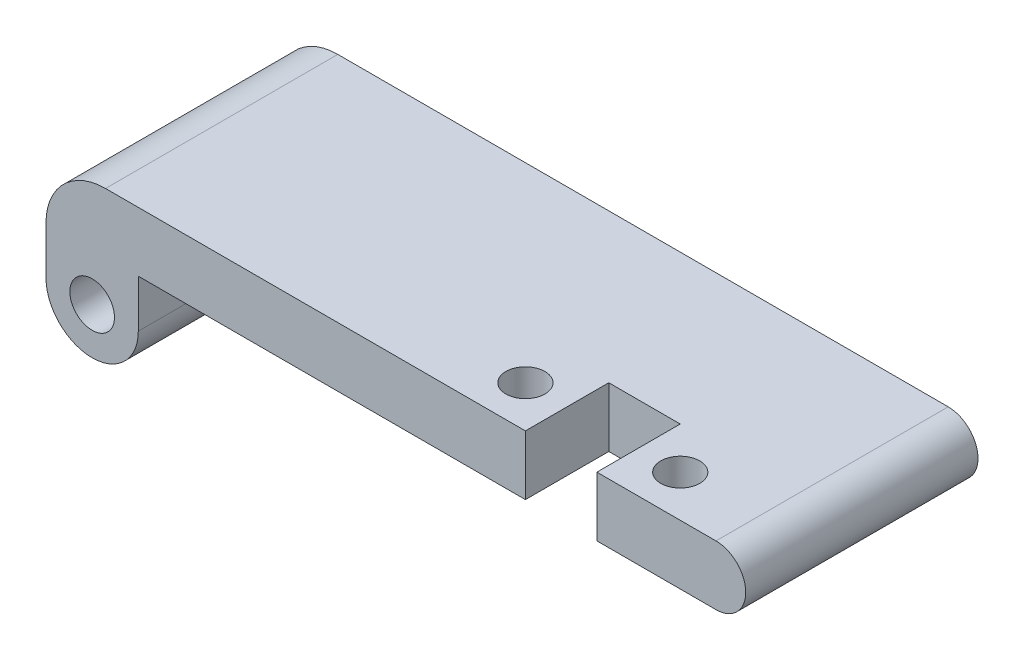
SolidWorks part; units mm, degrees
ref_plane "Front Plane" through (0, 0, 0) normal (0, 0, 1) x (1, 0, 0)
ref_plane "Top Plane" through (0, 0, 0) normal (0, 1, 0) x (1, 0, 0)
ref_plane "Right Plane" through (0, 0, 0) normal (1, 0, 0) x (0, 0, -1)
sketch "Sketch1" plane through (0, 0, 0) normal (0, 0, 1) x (1, 0, 0)
  line L0 (-37.3856, -8.255) -> (-37.3856, -3.175)
  line L1 (-37.3856, 3.175) -> (37.3856, 3.175)
  line L2 (-37.3856, 3.175) -> (-37.3856, -3.175)
  line L3 (-27.5431, -3.175) -> (37.3856, -3.175)
  line L4 (37.3856, 3.175) -> (37.3856, -3.175)
  line L5 (-37.3856, 3.175) -> (37.3856, -3.175) construction
  line L6 (-37.3856, -3.175) -> (37.3856, 3.175) construction
  line L7 (-27.5431, -8.255) -> (-27.5431, -3.175)
  circle A0 centre (-32.4644, -8.255) radius 2.3812
  arc A1 (-37.3856, -8.255) -> (-27.5431, -8.255) centre (-32.4644, -8.255) ccw
  point P0 (0, 0)
  dimension "D1" = 4.7625
  dimension "D3" = 2.54
  dimension "D2" = 6.35
  dimension "D4" = 69.85
  dimension "D5" = 5.08
extrude "Boss-Extrude1" add sketch "Sketch1" along normal blind 38.1
fillet "Fillet1" radius 6.35 1 edges at (-37.3856, 3.175, 19.05)
sketch "Sketch3" plane through (37.3856, 0, 0) normal (1, 0, 0) x (0, 0, -1)
  line L4 (0, -3.175) -> (0, 3.175)
  line L5 (0, 3.175) -> (-38.1, 3.175)
  line L6 (-38.1, 3.175) -> (-38.1, -3.175)
  line L7 (-38.1, -3.175) -> (0, -3.175)
  line L8 (0, -3.175) -> (0, 3.175)
  line L9 (0, 3.175) -> (-38.1, 3.175)
  line L10 (-38.1, 3.175) -> (-38.1, -3.175)
  line L11 (-38.1, -3.175) -> (0, -3.175)
  dimension "D1" = 0
extrude "Boss-Extrude2" add sketch "Sketch3" along normal blind 12.7
sketch "Sketch2" plane through (0, 3.175, 0) normal (0, 1, 0) x (1, 0, 0)
  line L1 (48.4981, -15.875) -> (11.9856, -15.875) construction
  line L2 (48.4981, -15.875) -> (48.4981, 0) construction
  line L3 (48.4981, 0) -> (11.9856, 0) construction
  line L4 (11.9856, -15.875) -> (11.9856, 0) construction
  line L5 (48.4981, -15.875) -> (11.9856, 0) construction
  line L6 (48.4981, 0) -> (11.9856, -15.875) construction
  line L7 (11.9856, -17.4625) -> (-16.5894, -17.4625) construction
  line L8 (11.9856, -17.4625) -> (11.9856, 1.5875) construction
  line L9 (11.9856, 1.5875) -> (-16.5894, 1.5875) construction
  line L10 (-16.5894, -17.4625) -> (-16.5894, 1.5875) construction
  line L11 (11.9856, -17.4625) -> (-16.5894, 1.5875) construction
  line L12 (11.9856, 1.5875) -> (-16.5894, -17.4625) construction
  line L13 (37.3856, -25.4) -> (37.3856, 9.525) construction
  line L14 (50.0856, 0) -> (-31.0356, 0) construction
  line L15 (-34.8456, -38.1) -> (-30.0831, -38.1) construction
  line L16 (-34.8456, -38.1) -> (-30.0831, -38.1) construction
  line L18 (21.3519, -24.765) -> (13.7319, -24.765)
  line L19 (21.3519, -24.765) -> (21.3519, -15.875)
  line L20 (21.3519, -15.875) -> (13.7319, -15.875)
  line L21 (13.7319, -24.765) -> (13.7319, -15.875)
  line L22 (21.3519, -24.765) -> (13.7319, -15.875) construction
  line L23 (21.3519, -15.875) -> (13.7319, -24.765) construction
  point P0 (30.2419, -7.9375)
  point P5 (17.5419, -20.32)
  point P6 (-2.3019, -7.9375)
  point P15 (17.5419, -20.32)
  point P21 (-32.4644, -38.1)
  point P26 (37.3856, -7.9375)
  dimension "Motor_Pos" = 15.875
  dimension "D2" = 36.5125
  dimension "D3" = 28.575
  dimension "D4" = 19.05
  dimension "D5" = 5.5562
  dimension "D6" = 11.1125
  dimension "D7" = 34.925
  dimension "D8" = 69.85
  dimension "D9" = 8.89
  dimension "D10" = 7.62
extrude "Cut-Extrude7" cut sketch "Sketch2" against normal through all
sketch "Sketch10" plane through (0, 3.175, 0) normal (0, 1, 0) x (1, 0, 0)
  line L0 (13.7319, -24.765) -> (13.7319, -15.875) construction
  line L1 (21.3519, -24.765) -> (13.7319, -24.765) construction
  line L2 (21.3519, -24.765) -> (21.3519, -15.875) construction
  line L3 (21.3519, -15.875) -> (13.7319, -15.875) construction
  line L12 (13.7319, -24.765) -> (13.7319, -15.875)
  line L13 (21.3519, -24.765) -> (13.7319, -24.765)
  line L14 (21.3519, -24.765) -> (21.3519, -15.875)
  line L15 (21.3519, -15.875) -> (13.7319, -15.875)
extrude "Boss-Extrude5" add sketch "Sketch10" along normal blind 22.225 and the other way blind 9.525
sketch "Sketch5" plane through (0, 0, 24.765) normal (0, 0, 1) x (1, 0, 0)
  line L0 (17.5419, 25.4) -> (17.5419, -6.35) construction
  line L3 (13.7319, -6.35) -> (21.3519, -6.35) construction
  line L4 (13.7319, 25.4) -> (21.3519, 25.4) construction
  circle A0 centre (17.5419, 5.715) radius 1.905
  circle A1 centre (17.5419, 23.1775) radius 1.905
  dimension "D1" = 3.81
  dimension "D2" = 17.4625
  dimension "D3" = 12.065
extrude "Cut-Extrude1" cut sketch "Sketch5" against normal through all both and the other way through all
sketch "Sketch6" plane through (0, -3.175, 0) normal (0, 1, 0) x (1, 0, 0)
  line L1 (30.2419, -24.765) -> (4.8419, -24.765)
  line L2 (30.2419, -24.765) -> (30.2419, -15.875)
  line L3 (30.2419, -15.875) -> (4.8419, -15.875)
  line L4 (4.8419, -24.765) -> (4.8419, -15.875)
  line L5 (30.2419, -24.765) -> (4.8419, -15.875) construction
  line L6 (30.2419, -15.875) -> (4.8419, -24.765) construction
  line L9 (4.8419, -24.765) -> (30.2419, -24.765) construction
  line L11 (21.3519, -15.875) -> (13.7319, -15.875) construction
  line L12 (21.3519, -24.765) -> (13.7319, -24.765) construction
  line L13 (21.3519, -24.765) -> (13.7319, -24.765)
  line L14 (13.7319, -24.765) -> (13.7319, -15.875) construction
  point P0 (17.5419, -20.32)
  point P14 (17.5419, -24.765)
  point P16 (17.5419, -24.765)
  line M22 (13.7319, -15.875) -> (13.7319, -24.765)
  line M24 (21.3519, -24.765) -> (21.3519, -15.875)
  dimension "D1" = 25.4
  dimension "D2" = 8.89
  dimension "D3" = 8.89
extrude "Boss-Extrude4" add sketch "Sketch6" against normal up to surface (3.175 mm away) contours L1 L4 L3 M22 | L3 L2 L1 M24 up to face at (17.5419, -6.35, 20.32)
sketch "Sketch7" plane through (0, -6.35, 0) normal (0, -1, 0) x (-1, 0, 0)
  line L1 (-4.8419, -24.765) -> (-13.7319, -24.765) construction
  line L2 (-4.8419, -24.765) -> (-4.8419, -15.875) construction
  line L3 (-4.8419, -15.875) -> (-13.7319, -15.875) construction
  line L4 (-13.7319, -24.765) -> (-13.7319, -15.875) construction
  line L5 (-4.8419, -24.765) -> (-13.7319, -15.875) construction
  line L6 (-4.8419, -15.875) -> (-13.7319, -24.765) construction
  line L10 (-17.5419, -24.765) -> (-17.5419, -15.875) construction
  line L12 (-4.8419, -24.765) -> (-30.2419, -24.765) construction
  line L13 (-30.2419, -15.875) -> (-4.8419, -15.875) construction
  line L14 (-4.8419, -24.765) -> (-4.8419, -15.875) construction
  line L15 (-21.3519, -24.765) -> (-21.3519, -15.875) construction
  line L16 (-13.7319, -24.765) -> (-21.3519, -24.765) construction
  line L17 (-13.7319, -15.875) -> (-13.7319, -24.765) construction
  line L18 (-21.3519, -15.875) -> (-13.7319, -15.875) construction
  line L19 (-21.3519, -24.765) -> (-21.3519, -15.875) construction
  line L20 (-13.7319, -24.765) -> (-21.3519, -24.765) construction
  line L21 (-13.7319, -15.875) -> (-13.7319, -24.765) construction
  line L22 (-21.3519, -15.875) -> (-13.7319, -15.875) construction
  circle A0 centre (-9.2869, -20.32) radius 2.0828
  circle A2 centre (-25.7969, -20.32) radius 2.0828
  point P14 (-17.5419, -24.765)
  dimension "D1" = 4.1656
extrude "Cut-Extrude2" cut sketch "Sketch7" against normal through all both and the other way through all
ref_plane "Plane1" through (-27.5431, -3.175, 38.1) normal (1, 0, 0) x (0, 0, -1)
sketch "Sketch9" plane through (0, 0, 38.1) normal (0, 0, 1) x (1, 0, 0)
  line L0 (50.0856, 3.175) -> (50.0856, -3.175) construction
  line L1 (-27.5431, -3.175) -> (50.0856, -3.175) construction
  line L2 (-27.5431, -8.255) -> (-27.5431, -3.175) construction
  line L3 (-37.3856, -3.175) -> (-37.3856, -8.255) construction
  line L4 (50.0856, 3.175) -> (-31.0356, 3.175) construction
  line L5 (50.0856, 3.175) -> (50.0856, -3.175)
  line L6 (-27.5431, -3.175) -> (50.0856, -3.175)
  line L7 (-27.5431, -8.255) -> (-27.5431, -3.175)
  line L8 (-37.3856, -3.175) -> (-37.3856, -8.255)
  line L9 (50.0856, 3.175) -> (-31.0356, 3.175)
  arc A0 (-37.3856, -8.255) -> (-27.5431, -8.255) centre (-32.4644, -8.255) ccw construction
  arc A1 (-31.0356, 3.175) -> (-37.3856, -3.175) centre (-31.0356, -3.175) ccw construction
  arc A2 (-37.3856, -8.255) -> (-27.5431, -8.255) centre (-32.4644, -8.255) ccw
  arc A3 (-31.0356, 3.175) -> (-37.3856, -3.175) centre (-31.0356, -3.175) ccw
extrude "Cut-Extrude8" cut sketch "Sketch9" against normal up to surface (13.335 mm away) up to face at (19.4469, 5.715, 24.765)
sketch "Sketch11" plane through (0, 25.4, 0) normal (0, 1, 0) x (1, 0, 0)
  line L4 (13.7319, -24.765) -> (21.3519, -24.765)
  line L5 (21.3519, -24.765) -> (21.3519, -15.875)
  line L6 (21.3519, -15.875) -> (13.7319, -15.875)
  line L7 (13.7319, -15.875) -> (13.7319, -24.765)
  line L8 (13.7319, -24.765) -> (21.3519, -24.765)
  line L9 (21.3519, -24.765) -> (21.3519, -15.875)
  line L10 (21.3519, -15.875) -> (13.7319, -15.875)
  line L11 (13.7319, -15.875) -> (13.7319, -24.765)
  dimension "D1" = 0
extrude "Cut-Extrude9" cut sketch "Sketch11" against normal through all
sketch "Sketch12" plane through (0, -6.35, 0) normal (0, -1, 0) x (1, 0, 0)
  line L4 (13.7319, 15.875) -> (13.7319, 24.765)
  line L5 (13.7319, 24.765) -> (4.8419, 24.765)
  line L6 (4.8419, 24.765) -> (4.8419, 15.875)
  line L7 (4.8419, 15.875) -> (13.7319, 15.875)
  line L8 (13.7319, 15.875) -> (13.7319, 24.765)
  line L9 (13.7319, 24.765) -> (4.8419, 24.765)
  line L10 (4.8419, 24.765) -> (4.8419, 15.875)
  line L11 (4.8419, 15.875) -> (13.7319, 15.875)
  line L12 (21.3519, 24.765) -> (21.3519, 15.875)
  line L13 (21.3519, 15.875) -> (30.2419, 15.875)
  line L14 (30.2419, 15.875) -> (30.2419, 24.765)
  line L15 (30.2419, 24.765) -> (21.3519, 24.765)
  line L16 (21.3519, 24.765) -> (21.3519, 15.875)
  line L17 (21.3519, 15.875) -> (30.2419, 15.875)
  line L18 (30.2419, 15.875) -> (30.2419, 24.765)
  line L19 (30.2419, 24.765) -> (21.3519, 24.765)
  dimension "D1" = 0
  dimension "D2" = 0
extrude "Cut-Extrude10" cut sketch "Sketch12" against normal up to surface (3.175 mm away) up to face at (15.0336, -3.175, 16.256)
sketch "Sketch13" plane through (0, 0, 24.765) normal (0, 0, 1) x (1, 0, 0)
  line L0 (21.3519, 3.175) -> (50.0856, 3.175) construction
  line L1 (50.0856, -3.175) -> (21.3519, -3.175) construction
  line L2 (21.3519, -3.175) -> (21.3519, 3.175) construction
  line L3 (34.0519, 3.175) -> (50.0856, 3.175)
  line L4 (50.0856, 3.175) -> (50.0856, -3.175)
  line L5 (50.0856, -3.175) -> (34.0519, -3.175)
  arc A0 (34.0519, -3.175) -> (34.0519, 3.175) centre (34.0519, 0) ccw
  dimension "D1" = 12.7
extrude "Cut-Extrude11" cut sketch "Sketch13" against normal through all
